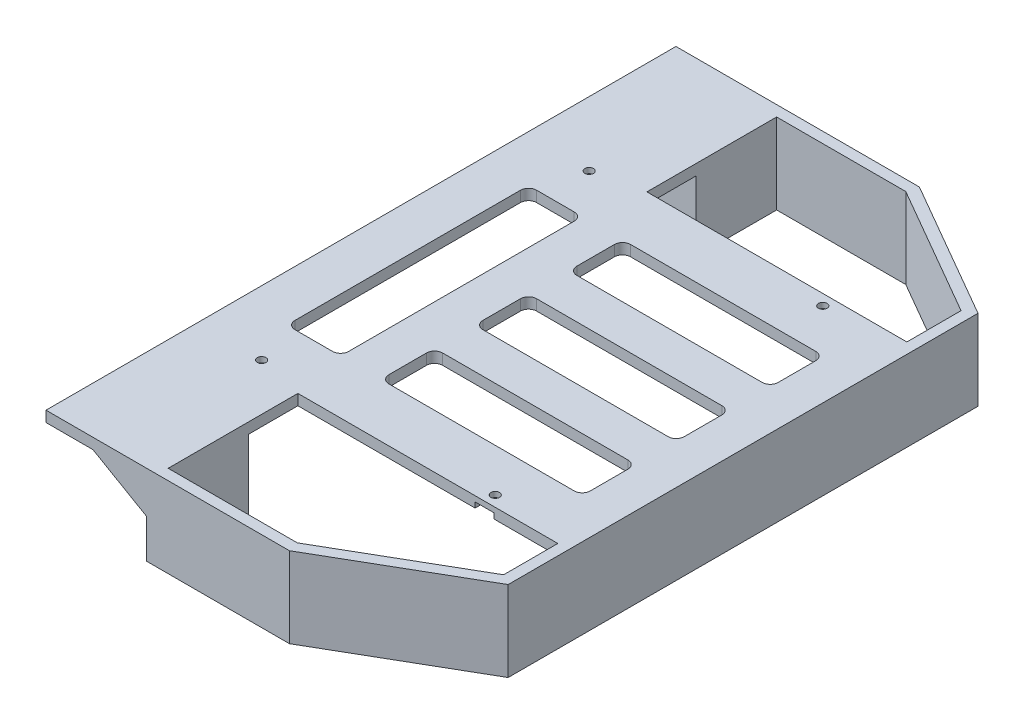
SolidWorks part; units mm, degrees
ref_plane "Front Plane" through (0, 0, 0) normal (0, 0, 1) x (1, 0, 0)
ref_plane "Top Plane" through (0, 0, 0) normal (0, 1, 0) x (1, 0, 0)
ref_plane "Right Plane" through (0, 0, 0) normal (1, 0, 0) x (0, 0, -1)
sketch "Sketch6" plane through (0, 0, 0) normal (0, 1, 0) x (1, 0, 0)
  line L0 (-142.3198, -87.5) -> (-142.3198, 87.5) construction
  line L1 (-142.3198, 87.5) -> (-90.67, 117.32) construction
  line L2 (-90.67, 117.32) -> (-37.5, 117.32) construction
  line L3 (-37.5, 117.32) -> (-37.5, 87.32) construction
  line L4 (-37.5, 87.32) -> (37.5, 87.32) construction
  line L5 (37.5, 87.32) -> (37.5, 117.32) construction
  line L6 (37.5, 117.32) -> (90.67, 117.32) construction
  line L7 (90.67, 117.32) -> (142.3198, 87.5) construction
  line L8 (142.3198, 87.5) -> (142.3198, -87.5) construction
  line L9 (-142.3198, 0) -> (142.3198, 0) construction
  line L10 (90.67, -117.32) -> (142.3198, -87.5) construction
  line L11 (37.5, -117.32) -> (90.67, -117.32) construction
  line L12 (-37.5, -87.32) -> (37.5, -87.32) construction
  line L13 (-37.5, -117.32) -> (-37.5, -87.32) construction
  line L14 (-90.67, -117.32) -> (-37.5, -117.32) construction
  line L15 (-142.3198, -87.5) -> (-90.67, -117.32) construction
  line L16 (37.5, -87.32) -> (37.5, -117.32) construction
  line L17 (0, -87.32) -> (37.5, -87.32)
  line L18 (37.5, -87.32) -> (37.5, -117.32)
  line L19 (37.5, -117.32) -> (90.67, -117.32)
  line L20 (90.67, -117.32) -> (142.3198, -87.5)
  line L21 (142.3198, -87.5) -> (142.3198, 87.5)
  line L23 (0, 87.32) -> (37.5, 87.32)
  line L24 (37.5, 87.32) -> (37.5, 117.32)
  line L25 (37.5, 117.32) -> (90.67, 117.32)
  line L26 (90.67, 117.32) -> (142.3198, 87.5)
  line L28 (0, -83.32) -> (41.5, -83.32)
  line L29 (41.5, -83.32) -> (41.5, -113.32)
  line L30 (41.5, -113.32) -> (89.5982, -113.32)
  line L31 (89.5982, -113.32) -> (138.3198, -85.1906)
  line L32 (138.3198, -85.1906) -> (138.3198, 85.1906)
  line L33 (89.5982, 113.32) -> (138.3198, 85.1906)
  line L34 (41.5, 113.32) -> (89.5982, 113.32)
  line L35 (41.5, 83.32) -> (41.5, 113.32)
  line L36 (0, 83.32) -> (41.5, 83.32)
  line L37 (0, 87.32) -> (0, 83.32)
  line L38 (0, -83.32) -> (0, -87.32)
  point P6 (0, 87.32)
  point P11 (0, 0)
  dimension "D1" = 30
  dimension "D2" = 75
  dimension "D3" = 53.17
  dimension "D4" = 87.5
  dimension "D5" = 59.64
  dimension "D6" = 120
  dimension "D7" = 4
extrude "Boss-Extrude1" add sketch "Sketch6" along normal blind 30
sketch "Sketch9" plane through (0, 0, 87.32) normal (0, 0, 1) x (1, 0, 0)
  line L0 (37.5, 0) -> (15, 8)
  line L1 (15, 8) -> (0, 8)
  line L2 (0, 30) -> (0, 0) construction
  line L3 (0, 0) -> (37.5, 0) construction
  line L4 (0, 8) -> (0, 0)
  line L5 (0, 0) -> (37.5, 0)
  dimension "D1" = 15
  dimension "D2" = 8
extrude "Cut-Extrude1" cut sketch "Sketch9" against normal up to next
sketch "Sketch10" plane through (0, 30, 0) normal (0, 1, 0) x (1, 0, 0)
  line L0 (37.5, -117.32) -> (90.67, -117.32) construction
  line L1 (0, -83.32) -> (41.5, -83.32)
  line L2 (0, -83.32) -> (0, -117.32)
  line L3 (0, -117.32) -> (41.5, -117.32)
  line L4 (41.5, -83.32) -> (41.5, -117.32)
  line L5 (41.5, -113.32) -> (41.5, -83.32) construction
extrude "Boss-Extrude3" add sketch "Sketch10" against normal blind 4
mirror "Mirror1" about plane through (0, 0, 0) normal (0, 0, 1) of "Boss-Extrude3", "Cut-Extrude1"
chamfer "Chamfer4" distance 20 angle 30 2 edges at (37.5, 26, 102.32) (37.5, 26, -102.32)
sketch "Sketch11" plane through (0, 30, 0) normal (0, 1, 0) x (1, 0, 0)
  line L0 (41.5, -83.32) -> (0, -83.32) construction
  line L1 (0, 83.32) -> (20.75, 83.32)
  line L2 (0, 83.32) -> (0, -83.32)
  line L3 (0, -83.32) -> (20.75, -83.32)
  line L4 (20.75, 83.32) -> (20.75, -83.32)
  point P8 (20.75, -83.32)
extrude "Boss-Extrude4" add sketch "Sketch11" against normal blind 4
sketch "Sketch12" plane through (0, 30, 0) normal (0, 1, 0) x (1, 0, 0)
  line L0 (20.75, -83.32) -> (20.75, 83.32) construction
  line L1 (20.75, 65) -> (138.3198, 65)
  line L2 (20.75, 65) -> (20.75, -65)
  line L3 (20.75, -65) -> (138.3198, -65)
  line L4 (138.3198, 65) -> (138.3198, -65)
  line L5 (138.3198, 85.1906) -> (138.3198, -85.1906) construction
  line L7 (41.5, 83.32) -> (20.75, 83.32)
  line L8 (41.5, 83.32) -> (41.5, 65)
  line L9 (41.5, 65) -> (20.75, 65)
  line L10 (20.75, 83.32) -> (20.75, 65)
  line L11 (41.5, -83.32) -> (20.75, -83.32)
  line L12 (41.5, -83.32) -> (41.5, -65)
  line L13 (41.5, -65) -> (20.75, -65)
  line L14 (20.75, -83.32) -> (20.75, -65)
  point P8 (20.75, 0)
  line M5 (41.5, -83.32) -> (20.75, -83.32)
  line M7 (20.75, -83.32) -> (20.75, 83.32)
  line M9 (20.75, 83.32) -> (41.5, 83.32)
  line M13 (138.3198, 85.1906) -> (138.3198, -85.1906)
  dimension "D1" = 130
extrude "Boss-Extrude5" add sketch "Sketch12" against normal blind 4 contours L3 L1 M7 M13 | L12 L3 M5 M7 | L8 L1 M9 M7
sketch "Sketch13" plane through (0, 30, 0) normal (0, 1, 0) x (1, 0, 0)
  line L14 (0, 0) -> (142.3198, 0) construction
  line L15 (52.4099, 45) -> (127.4099, 45)
  line L16 (52.4099, 45) -> (52.4099, 25)
  line L17 (52.4099, 25) -> (127.4099, 25)
  line L18 (127.4099, 45) -> (127.4099, 25)
  line L19 (52.4099, 10) -> (127.4099, 10)
  line L20 (52.4099, 10) -> (52.4099, -10)
  line L21 (52.4099, -10) -> (127.4099, -10)
  line L22 (127.4099, 10) -> (127.4099, -10)
  line L27 (142.3198, -87.5) -> (142.3198, 87.5) construction
  line L28 (41.5, 65) -> (138.3198, 65) construction
  line L29 (52.4099, -25) -> (127.4099, -25)
  line L30 (127.4099, -45) -> (127.4099, -25)
  line L31 (52.4099, -45) -> (127.4099, -45)
  line L32 (52.4099, -45) -> (52.4099, -25)
  line L42 (37.4099, 45) -> (17.4099, 45)
  line L43 (37.4099, 45) -> (37.4099, -45)
  line L44 (37.4099, -45) -> (17.4099, -45)
  line L45 (17.4099, 45) -> (17.4099, -45)
  point P12 (52.4099, 0)
  point P17 (89.9099, 65)
  point P20 (89.9099, 45)
  dimension "D1" = 75
  dimension "D2" = 20
  dimension "D3" = 15
  dimension "D4" = 15
extrude "Cut-Extrude2" cut sketch "Sketch13" against normal blind 4
fillet "Fillet1" radius 3 16 edges at (52.4099, 28, 45) (52.4099, 28, 10) (52.4099, 28, 25) (52.4099, 28, -10) (127.4099, 28, -10) (127.4099, 28, 25) (127.4099, 28, 45) (127.4099, 28, 10) (127.4099, 28, -25) (127.4099, 28, -45) (52.4099, 28, -25) (52.4099, 28, -45) (37.4099, 28, -45) (17.4099, 28, -45) (17.4099, 28, 45) (37.4099, 28, 45)
sketch "Sketch15" plane through (0, 30, 0) normal (0, 1, 0) x (1, 0, 0)
  line L1 (20, 65) -> (115, 65) construction
  line L2 (20, 65) -> (20, -65) construction
  line L3 (20, -65) -> (115, -65) construction
  line L4 (115, 65) -> (115, -65) construction
  circle A0 centre (111, 61) radius 1.6
  circle A1 centre (111, -61) radius 1.6
  circle A2 centre (24, -61) radius 1.6
  circle A3 centre (24, 61) radius 1.6
  point P4 (20, 0)
  point P14 (0, 0)
  point P15 (0, 0)
  point P16 (0, 0)
  point P17 (0, 0)
  point P18 (0, 0)
  point P20 (31.1595, 62.656)
  dimension "D4" = 3.2
  dimension "D1" = 95
  dimension "D2" = 130
  dimension "D3" = 20
  dimension "D5" = 4
  dimension "D6" = 4
  dimension "D7" = 4
  dimension "D8" = 4
extrude "Cut-Extrude3" cut sketch "Sketch15" against normal up to next
sketch "Sketch16" plane through (0, 26, 0) normal (0, -1, 0) x (1, 0, 0)
  line L0 (41.5, 65) -> (138.3198, 65) construction
  line L1 (107.5, 61) -> (114.5, 61)
  line L2 (107.5, 61) -> (107.5, 65)
  line L3 (107.5, 65) -> (114.5, 65)
  line L4 (114.5, 61) -> (114.5, 65)
  line L5 (41.5, -65) -> (138.3198, -65) construction
  line L6 (107.5, -61) -> (114.5, -61)
  line L7 (107.5, -61) -> (107.5, -65)
  line L8 (107.5, -65) -> (114.5, -65)
  line L9 (114.5, -61) -> (114.5, -65)
  circle A0 centre (24, 61) radius 3.5
  circle A1 centre (111, 61) radius 3.5
  circle A2 centre (111, -61) radius 3.5
  circle A3 centre (24, -61) radius 3.5
  circle M9 centre (24, -61) radius 1.6
  circle M10 centre (24, 61) radius 1.6
  circle M11 centre (111, 61) radius 1.6
  circle M12 centre (111, -61) radius 1.6
  line M48 (41.5, -65) -> (138.3198, -65)
  line M50 (138.3198, 65) -> (41.5, 65)
  dimension "D1" = 7
extrude "Cut-Extrude4" cut sketch "Sketch16" against normal blind 2 contours A0 M10 | L1 A1 M11 | L1 A1 M11 | A1 L4 L2 M50 | A2 L7 L9 M48 | L6 A2 M12 | L6 A2 M12 | A3 M9
